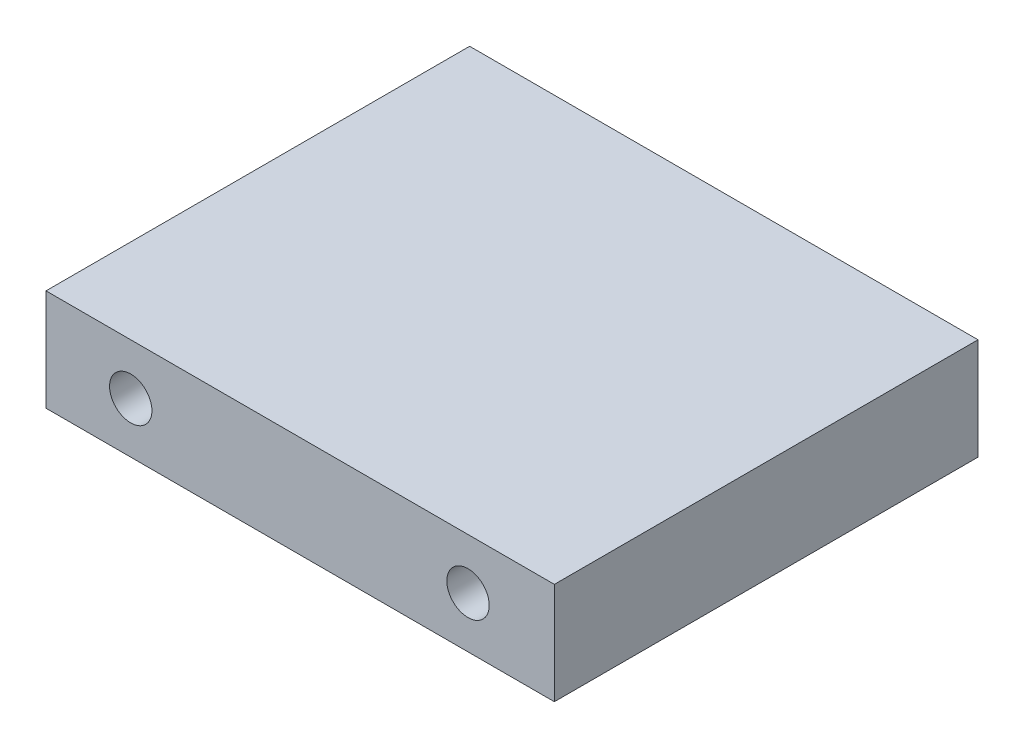
SolidWorks part; units mm, degrees
ref_plane "Plan de face" through (0, 0, 0) normal (0, 0, 1) x (1, 0, 0)
ref_plane "Plan de dessus" through (0, 0, 0) normal (0, 1, 0) x (1, 0, 0)
ref_plane "Plan de droite" through (0, 0, 0) normal (1, 0, 0) x (0, 0, -1)
sketch "Esquisse1" plane through (0, 0, 0) normal (0, 1, 0) x (1, 0, 0)
  line L1 (-15, -12.5) -> (15, -12.5)
  line L2 (-15, -12.5) -> (-15, 12.5)
  line L3 (-15, 12.5) -> (15, 12.5)
  line L4 (15, -12.5) -> (15, 12.5)
  line L5 (-15, -12.5) -> (15, 12.5) construction
  line L6 (-15, 12.5) -> (15, -12.5) construction
  point P0 (0, 0)
  dimension "D1" = 25
  dimension "D2" = 30
extrude "Boss.-Extru.1" add sketch "Esquisse1" along normal blind 6
sketch "Esquisse2" plane through (0, 0, 12.5) normal (0, 0, 1) x (1, 0, 0)
  line L0 (-10, 3) -> (-10, 6) construction
  line L1 (15, 3) -> (-15, 3) construction
  line L2 (15, 6) -> (15, 0) construction
  line L3 (-15, 6) -> (-15, 0) construction
  line L4 (10, 3) -> (10, 6) construction
  line L5 (-15, 6) -> (15, 6) construction
  point P0 (0, 3)
  dimension "D1" = 5
  dimension "D2" = 5
hole_wizard "Trou pour taraudage pour trou taraudé M31" positions "Esquisse4" profile "Esquisse3" hole size "M3" standard "ISO"
sketch "Esquisse4" plane through (0, 0, 12.5) normal (0, 0, 1) x (1, 0, 0)
  point P0 (-10, 3)
  point P4 (9.9039, 3.0037)
sketch "Esquisse3" plane through (-10, 3, 12.5) normal (1, 0, 0) x (0, -1, 0)
  line L0 (0, 0) -> (0, 10.7511)
  line L1 (0, 10.7511) -> (1.25, 10)
  line L2 (1.25, 10) -> (1.25, 0)
  line L5 (1.25, 0) -> (0, 0)
  line L10 (0, 10.7511) -> (-1.25, 10) construction
  line L11 (0, -6.35) -> (0, 107.95) construction
  dimension "Diamètre du perçage" = 2.5
  dimension "Profondeur du perçage" = 10
  dimension "Angle de pointe" = 118
sketch "Esquisse5" plane through (0, 0, -12.5) normal (0, 0, -1) x (-1, 0, 0)
  line L0 (0, 6) -> (0, 0) construction
  line L1 (-7.5, 3) -> (-7.5, 6) construction
  line L2 (-15, 3) -> (0, 3) construction
  line L3 (-15, 0) -> (15, 0) construction
  line L5 (-15, 6) -> (15, 6) construction
  line L7 (-15, 6) -> (-15, 0) construction
  line L9 (7.5, 3) -> (7.5, 6) construction
  line L10 (0, 3) -> (15, 3) construction
  line L11 (15, 6) -> (15, 0) construction
  dimension "D2" = 7.5
hole_wizard "Trou pour taraudage pour trou taraudé M33" positions "Esquisse9" profile "Esquisse8" hole size "M3" standard "ISO"
sketch "Esquisse9" plane through (0, 0, -12.5) normal (0, 0, -1) x (-1, 0, 0)
  point P0 (-7.5, 3)
  point P1 (7.5, 3)
sketch "Esquisse8" plane through (7.5, 3, -12.5) normal (1, 0, 0) x (0, 1, 0)
  line L0 (0, 0) -> (0, 11.7511)
  line L1 (0, 11.7511) -> (1.25, 11)
  line L2 (1.25, 11) -> (1.25, 0)
  line L5 (1.25, 0) -> (0, 0)
  line L10 (0, 11.7511) -> (-1.25, 11) construction
  line L11 (0, -6.35) -> (0, 107.95) construction
  dimension "Diamètre du perçage" = 2.5
  dimension "Profondeur du perçage" = 11
  dimension "Angle de pointe" = 118
